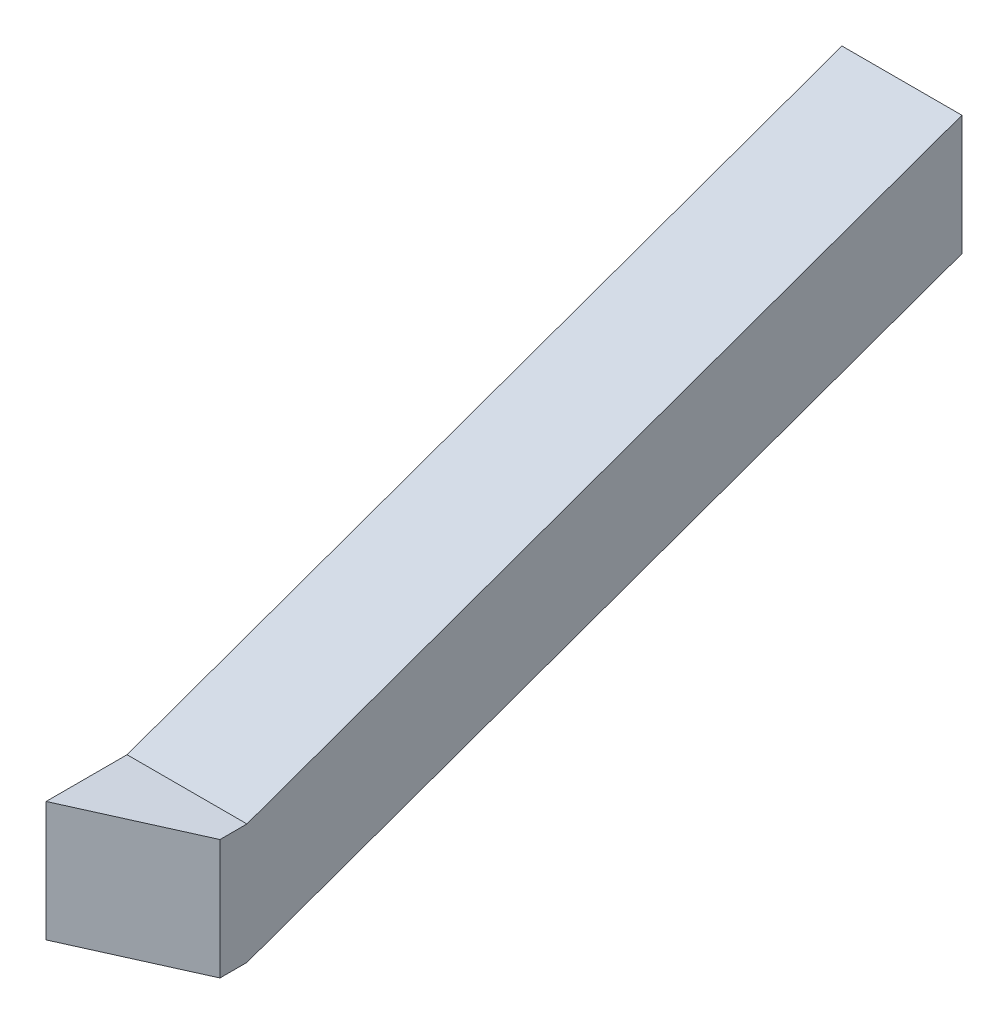
SolidWorks part; units mm, degrees
ref_plane "Alzado" through (0, 0, 0) normal (0, 0, 1) x (1, 0, 0)
ref_plane "Planta" through (0, 0, 0) normal (0, 1, 0) x (1, 0, 0)
ref_plane "Vista lateral" through (0, 0, 0) normal (1, 0, 0) x (0, 0, -1)
sketch "Croquis1" plane through (0, 0, 0) normal (0, 0, 1) x (1, 0, 0)
  line L1 (0, 0) -> (88.9, 0)
  line L2 (0, 0) -> (0, 88.9)
  line L3 (0, 88.9) -> (88.9, 88.9)
  line L4 (88.9, 0) -> (88.9, 88.9)
  dimension "D1" = 88.9
  dimension "D2" = 88.9
extrude "Saliente-Extruir1" add sketch "Croquis1" against normal blind 60
sketch3d "Croquis3D1"
  line L0 (44.45, 88.9, -60) -> (44.45, 0, -60) construction
  line L1 (88.9, 88.9, -60) -> (0, 88.9, -60) construction
  line L2 (0, 0, -60) -> (88.9, 0, -60) construction
  line L3 (44.45, 44.45, -60) -> (44.45, 44.45, -590) construction
  line L4 (44.45, 44.45, -590) -> (44.45, 234.45, -590) construction
  line L5 (44.45, 234.45, -590) -> (44.45, 44.45, -60)
  dimension "D1" = 530
  dimension "D2" = 190
sketch "Croquis2" plane through (0, 0, -60) normal (0, 0, -1) x (-1, 0, 0)
  line L1 (-88.9, 88.9) -> (0, 88.9)
  line L2 (-88.9, 88.9) -> (-88.9, 0)
  line L3 (-88.9, 0) -> (0, 0)
  line L4 (0, 88.9) -> (0, 0)
sweep "Barrer1" add profiles "Croquis2" path "Croquis3D1"
sketch "Croquis3" plane through (0, 88.9, 0) normal (0, 1, 0) x (1, 0, 0)
  line L0 (0, 0) -> (88.9, 40)
  line L1 (88.9, 60) -> (88.9, 0) construction
  line L2 (88.9, 40) -> (88.9, 0)
  line L3 (88.9, 0) -> (0, 0)
  dimension "D1" = 40
extrude "Cortar-Extruir1" cut sketch "Croquis3" against normal blind 100
